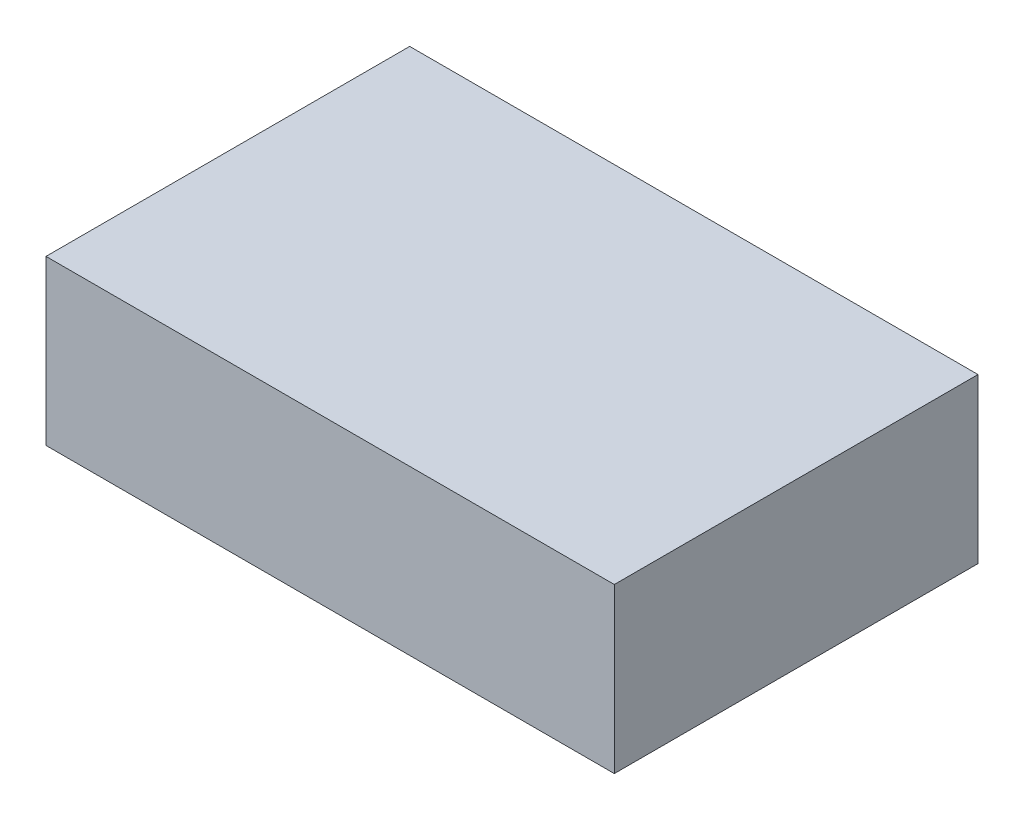
SolidWorks part; units mm, degrees
ref_plane "Front Plane" through (0, 0, 0) normal (0, 0, 1) x (1, 0, 0)
ref_plane "Top Plane" through (0, 0, 0) normal (0, 1, 0) x (1, 0, 0)
ref_plane "Right Plane" through (0, 0, 0) normal (1, 0, 0) x (0, 0, -1)
sketch "Sketch1" plane through (0, 0, 0) normal (0, 1, 0) x (1, 0, 0)
  line L1 (0, 0) -> (117.983, 0)
  line L2 (0, 0) -> (0, 75.5)
  line L3 (0, 75.5) -> (117.983, 75.5)
  line L4 (117.983, 0) -> (117.983, 75.5)
  dimension "D1" = 117.983
  dimension "D2" = 75.5
extrude "Boss-Extrude1" add sketch "Sketch1" along normal blind 34
